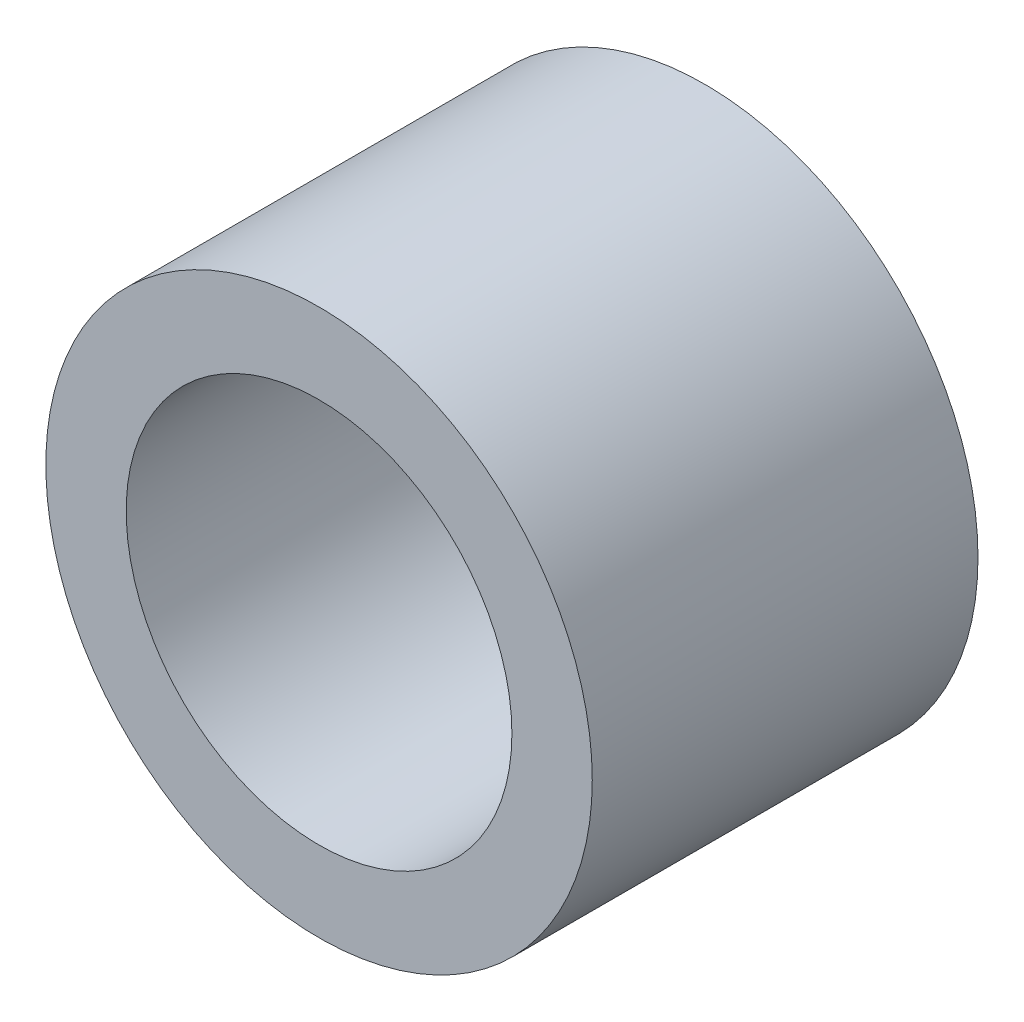
SolidWorks part; units mm, degrees
ref_plane "Front Plane" through (0, 0, 0) normal (0, 0, 1) x (1, 0, 0)
ref_plane "Top Plane" through (0, 0, 0) normal (0, 1, 0) x (1, 0, 0)
ref_plane "Right Plane" through (0, 0, 0) normal (1, 0, 0) x (0, 0, -1)
sketch "Sketch1" plane through (0, 0, 0) normal (0, 0, 1) x (1, 0, 0)
  circle A0 centre (0, 0) radius 3.4
  dimension "D1" = 6.8
extrude "Boss-Extrude1" add sketch "Sketch1" along normal blind 0.8
sketch "Sketch2" plane through (0, 0, 0.8) normal (0, 0, 1) x (1, 0, 0)
  circle A0 centre (0, 0) radius 3.4
  circle A1 centre (0, 0) radius 2.4
  circle A2 centre (0, 0) radius 3.4 construction
  dimension "D1" = 4.8
extrude "Boss-Extrude2" add sketch "Sketch2" along normal blind 4
